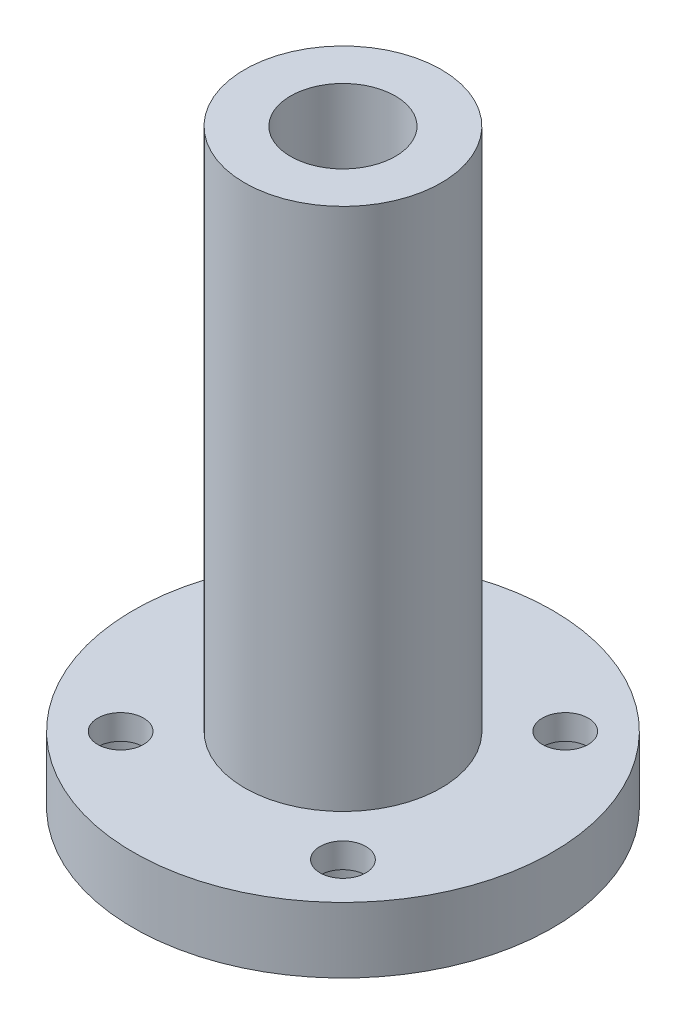
SolidWorks part; units mm, degrees
ref_plane "前视基准面" through (0, 0, 0) normal (0, 0, 1) x (1, 0, 0)
ref_plane "上视基准面" through (0, 0, 0) normal (0, 1, 0) x (1, 0, 0)
ref_plane "右视基准面" through (0, 0, 0) normal (1, 0, 0) x (0, 0, -1)
sketch "草图1" plane through (0, 0, 0) normal (0, 0, 1) x (1, 0, 0)
  line L0 (16, 5) -> (0, 5)
  line L1 (0, 5) -> (0, 0)
  line L2 (0, 0) -> (16, 0)
  line L3 (16, 0) -> (16, 5)
  line L4 (0, 5) -> (0, 0) construction
revolve "旋转1" add sketch "草图1" angle 360 about L4
sketch "草图2" plane through (0, 5, 0) normal (0, 1, 0) x (-1, 0, 0)
  circle A0 centre (0, 0) radius 7.5
extrude "凸台-拉伸1" add sketch "草图2" along normal blind 40
hole_wizard "M3 六角头机械螺钉的柱形沉头孔1" positions "草图4" profile "草图3" counterbore size "M3" standard "ANSI Metric"
sketch "草图4" plane through (0, 0, 0) normal (0, -1, 0) x (-1, 0, 0)
  point P0 (8.4853, 8.4853)
  point P1 (-8.4853, 8.4853)
  point P2 (-8.4853, -8.4853)
  point P3 (8.4853, -8.4853)
sketch "草图3" plane through (-8.4853, 0, -8.4853) normal (1, 0, 0) x (0, 0, -1)
  line L0 (0, 0) -> (0, 45)
  line L1 (0, 45) -> (1.75, 45)
  line L3 (1.75, 45) -> (1.75, 3.1)
  line L4 (1.75, 3.1) -> (3, 3.1)
  line L5 (3, 3.1) -> (3, 0)
  line L7 (3, 0) -> (0, 0)
  line L11 (0, -6.35) -> (0, 107.95) construction
  dimension "通孔孔直径" = 3.5
  dimension "通孔孔深度" = 45
  dimension "柱形沉头孔直径" = 6
  dimension "柱形沉头孔深度" = 3.1
hole_wizard "Ø8.0 (8) 直径孔1" positions "草图6" profile "草图5" hole size "Ø8.0" standard "ANSI Metric"
sketch "草图6" plane through (0, 0, 0) normal (0, -1, 0) x (-1, 0, 0)
  point P0 (0, 0)
sketch "草图5" plane through (0, 0, 0) normal (1, 0, 0) x (0, 0, -1)
  line L0 (0, 0) -> (0, 45)
  line L1 (0, 45) -> (4, 45)
  line L2 (4, 45) -> (4, 0)
  line L5 (4, 0) -> (0, 0)
  line L11 (0, -6.35) -> (0, 107.95) construction
  dimension "通孔孔直径" = 8
  dimension "通孔孔深度" = 45
